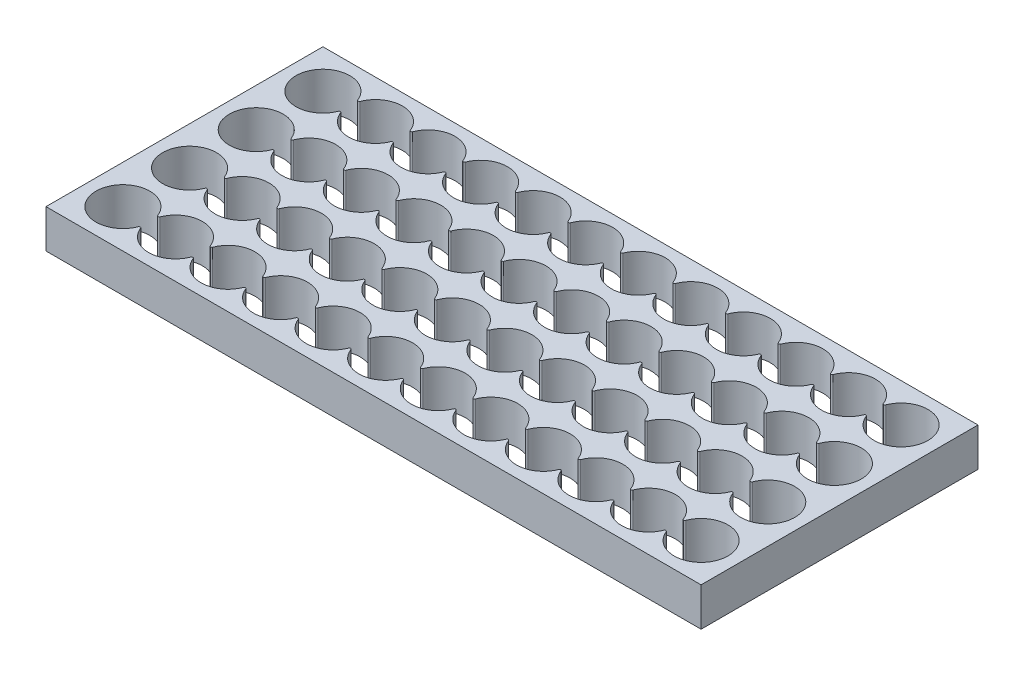
SolidWorks part; units mm, degrees
ref_plane "Front Plane" through (0, 0, 0) normal (0, 0, 1) x (1, 0, 0)
ref_plane "Top Plane" through (0, 0, 0) normal (0, 1, 0) x (1, 0, 0)
ref_plane "Right Plane" through (0, 0, 0) normal (1, 0, 0) x (0, 0, -1)
sketch "Sketch1" plane through (0, 0, 0) normal (0, 1, 0) x (1, 0, 0)
  line L0 (0, 0) -> (20.5, 0) construction
  line L2 (-15, -13) -> (240.5, -13) construction
  line L3 (-15, -13) -> (-15, 13)
  line L4 (-15, 13) -> (240.5, 13) construction
  line L5 (240.5, -13) -> (240.5, 39)
  line L6 (-15, 39) -> (240.5, 39) construction
  line L7 (0, 26) -> (20.5, 26) construction
  line L9 (-15, 65) -> (-15, 13)
  line L10 (0, 52) -> (20.5, 52) construction
  line L11 (-15, 65) -> (240.5, 65) construction
  line L12 (-15, 91) -> (240.5, 91) construction
  line L13 (0, 78) -> (20.5, 78) construction
  line L14 (240.5, 93) -> (240.5, 39)
  line L15 (-15, 93) -> (-15, 65)
  line L16 (-15, 93) -> (240.5, 93)
  line L17 (-15, -15) -> (240.5, -15)
  line L18 (240.5, -13) -> (240.5, -15)
  line L19 (-15, -13) -> (-15, -15)
  arc A23 (9.7841, 3.8107) -> (9.7841, -3.8107) centre (0, 0) ccw
  arc A25 (10.7159, -3.8107) -> (30.2841, -3.8107) centre (20.5, 0) ccw
  arc A26 (31.2159, -3.8107) -> (50.7841, -3.8107) centre (41, 0) ccw
  arc A27 (51.7159, -3.8107) -> (71.2841, -3.8107) centre (61.5, 0) ccw
  arc A28 (72.2159, -3.8107) -> (91.7841, -3.8107) centre (82, 0) ccw
  arc A29 (92.7159, -3.8107) -> (112.2841, -3.8107) centre (102.5, 0) ccw
  arc A30 (113.2159, -3.8107) -> (132.7841, -3.8107) centre (123, 0) ccw
  arc A31 (133.7159, -3.8107) -> (153.2841, -3.8107) centre (143.5, 0) ccw
  arc A32 (154.2159, -3.8107) -> (173.7841, -3.8107) centre (164, 0) ccw
  arc A33 (174.7159, -3.8107) -> (194.2841, -3.8107) centre (184.5, 0) ccw
  arc A34 (195.2159, -3.8107) -> (214.7841, -3.8107) centre (205, 0) ccw
  arc A35 (215.7159, -3.8107) -> (215.7159, 3.8107) centre (225.5, 0) ccw
  arc A36 (30.2841, 3.8107) -> (10.7159, 3.8107) centre (20.5, 0) ccw
  arc A37 (50.7841, 3.8107) -> (31.2159, 3.8107) centre (41, 0) ccw
  arc A38 (71.2841, 3.8107) -> (51.7159, 3.8107) centre (61.5, 0) ccw
  arc A39 (91.7841, 3.8107) -> (72.2159, 3.8107) centre (82, 0) ccw
  arc A40 (112.2841, 3.8107) -> (92.7159, 3.8107) centre (102.5, 0) ccw
  arc A41 (132.7841, 3.8107) -> (113.2159, 3.8107) centre (123, 0) ccw
  arc A42 (153.2841, 3.8107) -> (133.7159, 3.8107) centre (143.5, 0) ccw
  arc A43 (173.7841, 3.8107) -> (154.2159, 3.8107) centre (164, 0) ccw
  arc A44 (194.2841, 3.8107) -> (174.7159, 3.8107) centre (184.5, 0) ccw
  arc A45 (214.7841, 3.8107) -> (195.2159, 3.8107) centre (205, 0) ccw
  arc A46 (10.7159, 3.8107) -> (9.7841, 3.8107) centre (10.25, 3.9922) cw
  arc A47 (9.7841, -3.8107) -> (10.7159, -3.8107) centre (10.25, -3.9922) cw
  arc A48 (30.2841, -3.8107) -> (31.2159, -3.8107) centre (30.75, -3.9922) cw
  arc A49 (50.7841, -3.8107) -> (51.7159, -3.8107) centre (51.25, -3.9922) cw
  arc A50 (71.2841, -3.8107) -> (72.2159, -3.8107) centre (71.75, -3.9922) cw
  arc A51 (91.7841, -3.8107) -> (92.7159, -3.8107) centre (92.25, -3.9922) cw
  arc A52 (112.2841, -3.8107) -> (113.2159, -3.8107) centre (112.75, -3.9922) cw
  arc A53 (132.7841, -3.8107) -> (133.7159, -3.8107) centre (133.25, -3.9922) cw
  arc A54 (153.2841, -3.8107) -> (154.2159, -3.8107) centre (153.75, -3.9922) cw
  arc A55 (173.7841, -3.8107) -> (174.7159, -3.8107) centre (174.25, -3.9922) cw
  arc A56 (195.2159, -3.8107) -> (194.2841, -3.8107) centre (194.75, -3.9922) ccw
  arc A57 (214.7841, -3.8107) -> (215.7159, -3.8107) centre (215.25, -3.9922) cw
  arc A58 (215.7159, 3.8107) -> (214.7841, 3.8107) centre (215.25, 3.9922) cw
  arc A59 (195.2159, 3.8107) -> (194.2841, 3.8107) centre (194.75, 3.9922) cw
  arc A60 (174.7159, 3.8107) -> (173.7841, 3.8107) centre (174.25, 3.9922) cw
  arc A61 (154.2159, 3.8107) -> (153.2841, 3.8107) centre (153.75, 3.9922) cw
  arc A62 (133.7159, 3.8107) -> (132.7841, 3.8107) centre (133.25, 3.9922) cw
  arc A63 (113.2159, 3.8107) -> (112.2841, 3.8107) centre (112.75, 3.9922) cw
  arc A64 (92.7159, 3.8107) -> (91.7841, 3.8107) centre (92.25, 3.9922) cw
  arc A65 (72.2159, 3.8107) -> (71.2841, 3.8107) centre (71.75, 3.9922) cw
  arc A66 (51.7159, 3.8107) -> (50.7841, 3.8107) centre (51.25, 3.9922) cw
  arc A67 (31.2159, 3.8107) -> (30.2841, 3.8107) centre (30.75, 3.9922) cw
  arc A68 (31.2159, 22.1893) -> (30.2841, 22.1893) centre (30.75, 22.0078) ccw
  arc A69 (51.7159, 22.1893) -> (50.7841, 22.1893) centre (51.25, 22.0078) ccw
  arc A70 (72.2159, 22.1893) -> (71.2841, 22.1893) centre (71.75, 22.0078) ccw
  arc A71 (92.7159, 22.1893) -> (91.7841, 22.1893) centre (92.25, 22.0078) ccw
  arc A72 (113.2159, 22.1893) -> (112.2841, 22.1893) centre (112.75, 22.0078) ccw
  arc A73 (133.7159, 22.1893) -> (132.7841, 22.1893) centre (133.25, 22.0078) ccw
  arc A74 (154.2159, 22.1893) -> (153.2841, 22.1893) centre (153.75, 22.0078) ccw
  arc A75 (174.7159, 22.1893) -> (173.7841, 22.1893) centre (174.25, 22.0078) ccw
  arc A76 (195.2159, 22.1893) -> (194.2841, 22.1893) centre (194.75, 22.0078) ccw
  arc A77 (215.7159, 22.1893) -> (214.7841, 22.1893) centre (215.25, 22.0078) ccw
  arc A78 (214.7841, 29.8107) -> (215.7159, 29.8107) centre (215.25, 29.9922) ccw
  arc A79 (195.2159, 29.8107) -> (194.2841, 29.8107) centre (194.75, 29.9922) cw
  arc A80 (173.7841, 29.8107) -> (174.7159, 29.8107) centre (174.25, 29.9922) ccw
  arc A81 (153.2841, 29.8107) -> (154.2159, 29.8107) centre (153.75, 29.9922) ccw
  arc A82 (132.7841, 29.8107) -> (133.7159, 29.8107) centre (133.25, 29.9922) ccw
  arc A83 (112.2841, 29.8107) -> (113.2159, 29.8107) centre (112.75, 29.9922) ccw
  arc A84 (91.7841, 29.8107) -> (92.7159, 29.8107) centre (92.25, 29.9922) ccw
  arc A85 (71.2841, 29.8107) -> (72.2159, 29.8107) centre (71.75, 29.9922) ccw
  arc A86 (50.7841, 29.8107) -> (51.7159, 29.8107) centre (51.25, 29.9922) ccw
  arc A87 (30.2841, 29.8107) -> (31.2159, 29.8107) centre (30.75, 29.9922) ccw
  arc A88 (9.7841, 29.8107) -> (10.7159, 29.8107) centre (10.25, 29.9922) ccw
  arc A89 (10.7159, 22.1893) -> (9.7841, 22.1893) centre (10.25, 22.0078) ccw
  arc A90 (214.7841, 22.1893) -> (195.2159, 22.1893) centre (205, 26) cw
  arc A91 (194.2841, 22.1893) -> (174.7159, 22.1893) centre (184.5, 26) cw
  arc A92 (173.7841, 22.1893) -> (154.2159, 22.1893) centre (164, 26) cw
  arc A93 (153.2841, 22.1893) -> (133.7159, 22.1893) centre (143.5, 26) cw
  arc A94 (132.7841, 22.1893) -> (113.2159, 22.1893) centre (123, 26) cw
  arc A95 (112.2841, 22.1893) -> (92.7159, 22.1893) centre (102.5, 26) cw
  arc A96 (91.7841, 22.1893) -> (72.2159, 22.1893) centre (82, 26) cw
  arc A97 (71.2841, 22.1893) -> (51.7159, 22.1893) centre (61.5, 26) cw
  arc A98 (50.7841, 22.1893) -> (31.2159, 22.1893) centre (41, 26) cw
  arc A99 (30.2841, 22.1893) -> (10.7159, 22.1893) centre (20.5, 26) cw
  arc A100 (215.7159, 29.8107) -> (215.7159, 22.1893) centre (225.5, 26) cw
  arc A101 (195.2159, 29.8107) -> (214.7841, 29.8107) centre (205, 26) cw
  arc A102 (174.7159, 29.8107) -> (194.2841, 29.8107) centre (184.5, 26) cw
  arc A103 (154.2159, 29.8107) -> (173.7841, 29.8107) centre (164, 26) cw
  arc A104 (133.7159, 29.8107) -> (153.2841, 29.8107) centre (143.5, 26) cw
  arc A105 (113.2159, 29.8107) -> (132.7841, 29.8107) centre (123, 26) cw
  arc A106 (92.7159, 29.8107) -> (112.2841, 29.8107) centre (102.5, 26) cw
  arc A107 (72.2159, 29.8107) -> (91.7841, 29.8107) centre (82, 26) cw
  arc A108 (51.7159, 29.8107) -> (71.2841, 29.8107) centre (61.5, 26) cw
  arc A109 (31.2159, 29.8107) -> (50.7841, 29.8107) centre (41, 26) cw
  arc A110 (10.7159, 29.8107) -> (30.2841, 29.8107) centre (20.5, 26) cw
  arc A111 (9.7841, 22.1893) -> (9.7841, 29.8107) centre (0, 26) cw
  arc A112 (9.7841, 55.8107) -> (9.7841, 48.1893) centre (0, 52) ccw
  arc A113 (10.7159, 48.1893) -> (30.2841, 48.1893) centre (20.5, 52) ccw
  arc A114 (31.2159, 48.1893) -> (50.7841, 48.1893) centre (41, 52) ccw
  arc A115 (51.7159, 48.1893) -> (71.2841, 48.1893) centre (61.5, 52) ccw
  arc A116 (72.2159, 48.1893) -> (91.7841, 48.1893) centre (82, 52) ccw
  arc A117 (92.7159, 48.1893) -> (112.2841, 48.1893) centre (102.5, 52) ccw
  arc A118 (113.2159, 48.1893) -> (132.7841, 48.1893) centre (123, 52) ccw
  arc A119 (133.7159, 48.1893) -> (153.2841, 48.1893) centre (143.5, 52) ccw
  arc A120 (154.2159, 48.1893) -> (173.7841, 48.1893) centre (164, 52) ccw
  arc A121 (174.7159, 48.1893) -> (194.2841, 48.1893) centre (184.5, 52) ccw
  arc A122 (195.2159, 48.1893) -> (214.7841, 48.1893) centre (205, 52) ccw
  arc A123 (215.7159, 48.1893) -> (215.7159, 55.8107) centre (225.5, 52) ccw
  arc A124 (30.2841, 55.8107) -> (10.7159, 55.8107) centre (20.5, 52) ccw
  arc A125 (50.7841, 55.8107) -> (31.2159, 55.8107) centre (41, 52) ccw
  arc A126 (71.2841, 55.8107) -> (51.7159, 55.8107) centre (61.5, 52) ccw
  arc A127 (91.7841, 55.8107) -> (72.2159, 55.8107) centre (82, 52) ccw
  arc A128 (112.2841, 55.8107) -> (92.7159, 55.8107) centre (102.5, 52) ccw
  arc A129 (132.7841, 55.8107) -> (113.2159, 55.8107) centre (123, 52) ccw
  arc A130 (153.2841, 55.8107) -> (133.7159, 55.8107) centre (143.5, 52) ccw
  arc A131 (173.7841, 55.8107) -> (154.2159, 55.8107) centre (164, 52) ccw
  arc A132 (194.2841, 55.8107) -> (174.7159, 55.8107) centre (184.5, 52) ccw
  arc A133 (214.7841, 55.8107) -> (195.2159, 55.8107) centre (205, 52) ccw
  arc A134 (10.7159, 55.8107) -> (9.7841, 55.8107) centre (10.25, 55.9922) cw
  arc A135 (9.7841, 48.1893) -> (10.7159, 48.1893) centre (10.25, 48.0078) cw
  arc A136 (30.2841, 48.1893) -> (31.2159, 48.1893) centre (30.75, 48.0078) cw
  arc A137 (50.7841, 48.1893) -> (51.7159, 48.1893) centre (51.25, 48.0078) cw
  arc A138 (71.2841, 48.1893) -> (72.2159, 48.1893) centre (71.75, 48.0078) cw
  arc A139 (91.7841, 48.1893) -> (92.7159, 48.1893) centre (92.25, 48.0078) cw
  arc A140 (112.2841, 48.1893) -> (113.2159, 48.1893) centre (112.75, 48.0078) cw
  arc A141 (132.7841, 48.1893) -> (133.7159, 48.1893) centre (133.25, 48.0078) cw
  arc A142 (153.2841, 48.1893) -> (154.2159, 48.1893) centre (153.75, 48.0078) cw
  arc A143 (173.7841, 48.1893) -> (174.7159, 48.1893) centre (174.25, 48.0078) cw
  arc A144 (195.2159, 48.1893) -> (194.2841, 48.1893) centre (194.75, 48.0078) ccw
  arc A145 (214.7841, 48.1893) -> (215.7159, 48.1893) centre (215.25, 48.0078) cw
  arc A146 (215.7159, 55.8107) -> (214.7841, 55.8107) centre (215.25, 55.9922) cw
  arc A147 (195.2159, 55.8107) -> (194.2841, 55.8107) centre (194.75, 55.9922) cw
  arc A148 (174.7159, 55.8107) -> (173.7841, 55.8107) centre (174.25, 55.9922) cw
  arc A149 (154.2159, 55.8107) -> (153.2841, 55.8107) centre (153.75, 55.9922) cw
  arc A150 (133.7159, 55.8107) -> (132.7841, 55.8107) centre (133.25, 55.9922) cw
  arc A151 (113.2159, 55.8107) -> (112.2841, 55.8107) centre (112.75, 55.9922) cw
  arc A152 (92.7159, 55.8107) -> (91.7841, 55.8107) centre (92.25, 55.9922) cw
  arc A153 (72.2159, 55.8107) -> (71.2841, 55.8107) centre (71.75, 55.9922) cw
  arc A154 (51.7159, 55.8107) -> (50.7841, 55.8107) centre (51.25, 55.9922) cw
  arc A155 (31.2159, 55.8107) -> (30.2841, 55.8107) centre (30.75, 55.9922) cw
  arc A156 (31.2159, 74.1893) -> (30.2841, 74.1893) centre (30.75, 74.0078) ccw
  arc A157 (51.7159, 74.1893) -> (50.7841, 74.1893) centre (51.25, 74.0078) ccw
  arc A158 (72.2159, 74.1893) -> (71.2841, 74.1893) centre (71.75, 74.0078) ccw
  arc A159 (92.7159, 74.1893) -> (91.7841, 74.1893) centre (92.25, 74.0078) ccw
  arc A160 (113.2159, 74.1893) -> (112.2841, 74.1893) centre (112.75, 74.0078) ccw
  arc A161 (133.7159, 74.1893) -> (132.7841, 74.1893) centre (133.25, 74.0078) ccw
  arc A162 (154.2159, 74.1893) -> (153.2841, 74.1893) centre (153.75, 74.0078) ccw
  arc A163 (174.7159, 74.1893) -> (173.7841, 74.1893) centre (174.25, 74.0078) ccw
  arc A164 (195.2159, 74.1893) -> (194.2841, 74.1893) centre (194.75, 74.0078) ccw
  arc A165 (215.7159, 74.1893) -> (214.7841, 74.1893) centre (215.25, 74.0078) ccw
  arc A166 (214.7841, 81.8107) -> (215.7159, 81.8107) centre (215.25, 81.9922) ccw
  arc A167 (195.2159, 81.8107) -> (194.2841, 81.8107) centre (194.75, 81.9922) cw
  arc A168 (173.7841, 81.8107) -> (174.7159, 81.8107) centre (174.25, 81.9922) ccw
  arc A169 (153.2841, 81.8107) -> (154.2159, 81.8107) centre (153.75, 81.9922) ccw
  arc A170 (132.7841, 81.8107) -> (133.7159, 81.8107) centre (133.25, 81.9922) ccw
  arc A171 (112.2841, 81.8107) -> (113.2159, 81.8107) centre (112.75, 81.9922) ccw
  arc A172 (91.7841, 81.8107) -> (92.7159, 81.8107) centre (92.25, 81.9922) ccw
  arc A173 (71.2841, 81.8107) -> (72.2159, 81.8107) centre (71.75, 81.9922) ccw
  arc A174 (50.7841, 81.8107) -> (51.7159, 81.8107) centre (51.25, 81.9922) ccw
  arc A175 (30.2841, 81.8107) -> (31.2159, 81.8107) centre (30.75, 81.9922) ccw
  arc A176 (9.7841, 81.8107) -> (10.7159, 81.8107) centre (10.25, 81.9922) ccw
  arc A177 (10.7159, 74.1893) -> (9.7841, 74.1893) centre (10.25, 74.0078) ccw
  arc A178 (214.7841, 74.1893) -> (195.2159, 74.1893) centre (205, 78) cw
  arc A179 (194.2841, 74.1893) -> (174.7159, 74.1893) centre (184.5, 78) cw
  arc A180 (173.7841, 74.1893) -> (154.2159, 74.1893) centre (164, 78) cw
  arc A181 (153.2841, 74.1893) -> (133.7159, 74.1893) centre (143.5, 78) cw
  arc A182 (132.7841, 74.1893) -> (113.2159, 74.1893) centre (123, 78) cw
  arc A183 (112.2841, 74.1893) -> (92.7159, 74.1893) centre (102.5, 78) cw
  arc A184 (91.7841, 74.1893) -> (72.2159, 74.1893) centre (82, 78) cw
  arc A185 (71.2841, 74.1893) -> (51.7159, 74.1893) centre (61.5, 78) cw
  arc A186 (50.7841, 74.1893) -> (31.2159, 74.1893) centre (41, 78) cw
  arc A187 (30.2841, 74.1893) -> (10.7159, 74.1893) centre (20.5, 78) cw
  arc A188 (215.7159, 81.8107) -> (215.7159, 74.1893) centre (225.5, 78) cw
  arc A189 (195.2159, 81.8107) -> (214.7841, 81.8107) centre (205, 78) cw
  arc A190 (174.7159, 81.8107) -> (194.2841, 81.8107) centre (184.5, 78) cw
  arc A191 (154.2159, 81.8107) -> (173.7841, 81.8107) centre (164, 78) cw
  arc A192 (133.7159, 81.8107) -> (153.2841, 81.8107) centre (143.5, 78) cw
  arc A193 (113.2159, 81.8107) -> (132.7841, 81.8107) centre (123, 78) cw
  arc A194 (92.7159, 81.8107) -> (112.2841, 81.8107) centre (102.5, 78) cw
  arc A195 (72.2159, 81.8107) -> (91.7841, 81.8107) centre (82, 78) cw
  arc A196 (51.7159, 81.8107) -> (71.2841, 81.8107) centre (61.5, 78) cw
  arc A197 (31.2159, 81.8107) -> (50.7841, 81.8107) centre (41, 78) cw
  arc A198 (10.7159, 81.8107) -> (30.2841, 81.8107) centre (20.5, 78) cw
  arc A199 (9.7841, 74.1893) -> (9.7841, 81.8107) centre (0, 78) cw
  point P62 (215.25, 2.2776)
  point P65 (194.75, 2.2776)
  point P68 (174.25, 2.2776)
  point P71 (153.75, 2.2776)
  point P74 (133.25, 2.2776)
  point P77 (112.75, 2.2776)
  point P80 (92.25, 2.2776)
  point P83 (71.75, 2.2776)
  point P86 (51.25, 2.2776)
  point P89 (30.75, 2.2776)
  point P94 (-15, 0)
  point P176 (30.75, 23.7224)
  point P177 (51.25, 23.7224)
  point P178 (71.75, 23.7224)
  point P179 (92.25, 23.7224)
  point P180 (112.75, 23.7224)
  point P181 (133.25, 23.7224)
  point P182 (153.75, 23.7224)
  point P183 (174.25, 23.7224)
  point P184 (194.75, 23.7224)
  point P185 (215.25, 23.7224)
  point P346 (215.25, 54.2776)
  point P347 (194.75, 54.2776)
  point P348 (174.25, 54.2776)
  point P349 (153.75, 54.2776)
  point P350 (133.25, 54.2776)
  point P351 (112.75, 54.2776)
  point P352 (92.25, 54.2776)
  point P353 (71.75, 54.2776)
  point P354 (51.25, 54.2776)
  point P355 (30.75, 54.2776)
  point P356 (30.75, 75.7224)
  point P357 (51.25, 75.7224)
  point P358 (71.75, 75.7224)
  point P359 (92.25, 75.7224)
  point P360 (112.75, 75.7224)
  point P361 (133.25, 75.7224)
  point P362 (153.75, 75.7224)
  point P363 (174.25, 75.7224)
  point P364 (194.75, 75.7224)
  point P365 (215.25, 75.7224)
  dimension "D1" = 21
  dimension "D2" = 12
  dimension "D7" = 15
  dimension "D4" = 0.5
  dimension "D5" = 0.5
  dimension "D3" = 20.5
  dimension "D6" = 26
  dimension "D8" = 15
  dimension "D9" = 15
  dimension "D10" = 15
extrude "Boss-Extrude1" add sketch "Sketch1" along normal mid plane 15 contours L3 L19 L17 L18 L5 L14 L16 L15 L9 A155 A125 A154 A126 A153 A127 A152 A128 A151 A129 A150 A130 A149 A131 A148 A132 A147 A133 A146 A123 A145 A122 A144 A121 A143 A120 A142 A119 A141 A118 A140 A117 A139 A116 A138 A115 A137 A114 A136 A113 A135
